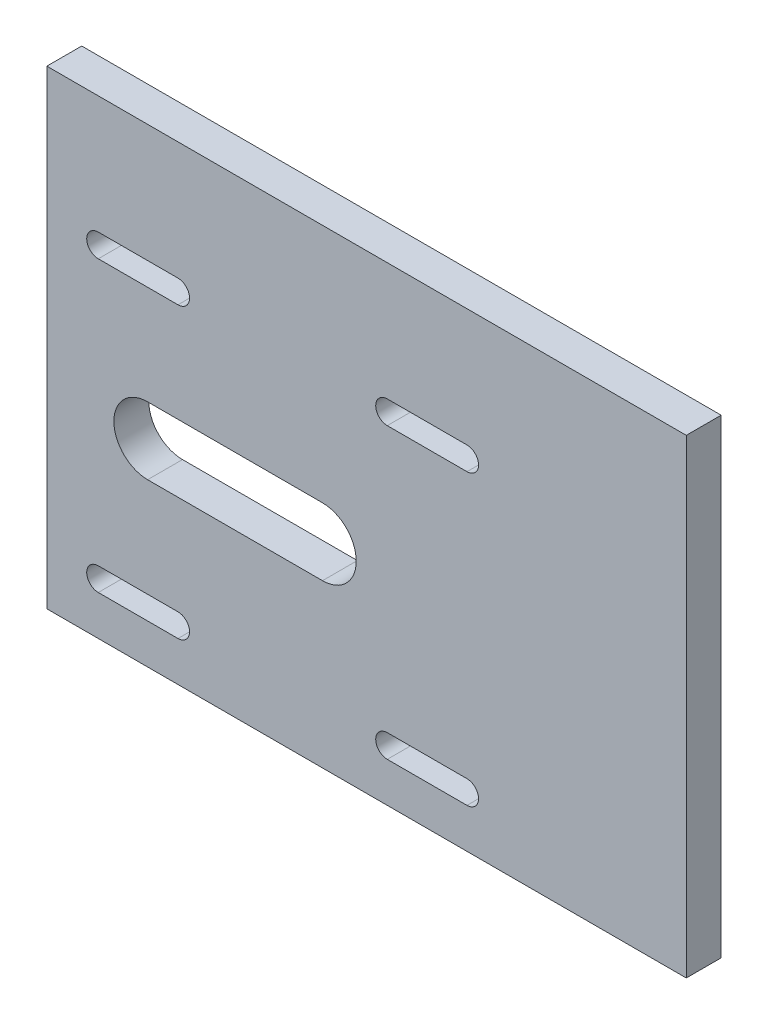
SolidWorks part; units mm, degrees
ref_plane "Front Plane" through (0, 0, 0) normal (0, 0, 1) x (1, 0, 0)
ref_plane "Top Plane" through (0, 0, 0) normal (0, 1, 0) x (1, 0, 0)
ref_plane "Right Plane" through (0, 0, 0) normal (1, 0, 0) x (0, 0, -1)
sketch "Sketch1" plane through (0, 0, 0) normal (0, 0, 1) x (1, 0, 0)
  line L1 (-80.8355, 31.4462) -> (-284.5572, 31.4462)
  line L2 (-80.8355, 31.4462) -> (-80.8355, -118.2868)
  line L3 (-80.8355, -118.2868) -> (-284.5572, -118.2868)
  line L4 (-284.5572, 31.4462) -> (-284.5572, -118.2868)
  line L5 (-242.7742, -101.9038) -> (-268.1742, -101.9038) construction
  line L6 (-242.7742, -105.5868) -> (-268.1742, -105.5868)
  line L7 (-242.7742, -98.2208) -> (-268.1742, -98.2208)
  line L8 (-242.7742, -9.8288) -> (-268.1742, -9.8288) construction
  line L9 (-242.7742, -13.5118) -> (-268.1742, -13.5118)
  line L10 (-242.7742, -6.1458) -> (-268.1742, -6.1458)
  line L11 (-150.6992, -9.8288) -> (-176.0992, -9.8288) construction
  line L12 (-150.6992, -13.5118) -> (-176.0992, -13.5118)
  line L13 (-150.6992, -6.1458) -> (-176.0992, -6.1458)
  line L14 (-150.6992, -101.9038) -> (-176.0992, -101.9038) construction
  line L15 (-150.6992, -105.5868) -> (-176.0992, -105.5868)
  line L16 (-150.6992, -98.2208) -> (-176.0992, -98.2208)
  line L17 (-196.7367, -55.8663) -> (-252.4523, -55.8663) construction
  line L18 (-196.7367, -66.6107) -> (-252.4523, -66.6107)
  line L19 (-196.7367, -45.122) -> (-252.4523, -45.122)
  line L20 (49.2125, 31.4462) -> (-99.8992, 31.4462) construction
  arc A0 (-77.6517, 0.6843) -> (-77.659, -0.2816) centre (-50.9905, 0) ccw construction
  circle A1 centre (-150.6992, -101.9038) radius 2.413 construction
  circle A2 centre (-150.6992, -101.9038) radius 2.413 construction
  circle A3 centre (-150.6992, -101.9038) radius 3.683 construction
  circle A4 centre (-242.7742, -101.9038) radius 3.683 construction
  circle A5 centre (-242.7742, -9.8288) radius 3.683 construction
  circle A6 centre (-150.6992, -9.8288) radius 3.683 construction
  arc A7 (-242.7742, -105.5868) -> (-242.7742, -98.2208) centre (-242.7742, -101.9038) ccw
  arc A8 (-268.1742, -98.2208) -> (-268.1742, -105.5868) centre (-268.1742, -101.9038) ccw
  arc A9 (-242.7742, -13.5118) -> (-242.7742, -6.1458) centre (-242.7742, -9.8288) ccw
  arc A10 (-268.1742, -6.1458) -> (-268.1742, -13.5118) centre (-268.1742, -9.8288) ccw
  arc A11 (-150.6992, -13.5118) -> (-150.6992, -6.1458) centre (-150.6992, -9.8288) ccw
  arc A12 (-176.0992, -6.1458) -> (-176.0992, -13.5118) centre (-176.0992, -9.8288) ccw
  arc A13 (-150.6992, -105.5868) -> (-150.6992, -98.2208) centre (-150.6992, -101.9038) ccw
  arc A14 (-176.0992, -98.2208) -> (-176.0992, -105.5868) centre (-176.0992, -101.9038) ccw
  arc A15 (-196.7367, -66.6107) -> (-196.7367, -45.122) centre (-196.7367, -55.8663) ccw
  arc A16 (-252.4523, -45.122) -> (-252.4523, -66.6107) centre (-252.4523, -55.8663) ccw
  point P4 (-80.8355, 31.4462)
  point P25 (-255.4742, -101.9038)
  point P31 (-255.4742, -9.8288)
  point P37 (-163.3992, -9.8288)
  point P43 (-163.3992, -101.9038)
  point P51 (-224.5945, -55.8663)
  dimension "D1" = 3.175
  dimension "D2" = 1.27
  dimension "D3" = 12.7
  dimension "D4" = 25.4
  dimension "D5" = 12.7
extrude "Boss-Extrude1" add sketch "Sketch1" along normal blind 11.1125
